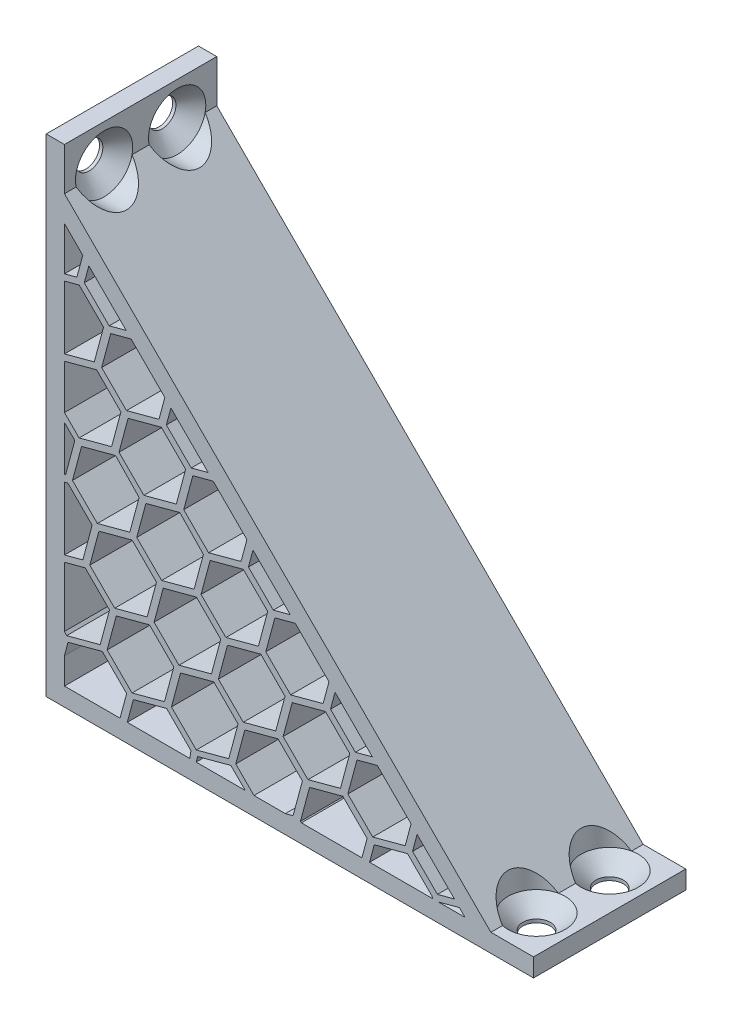
SolidWorks part; units mm, degrees
ref_plane "Front Plane" through (0, 0, 0) normal (0, 0, 1) x (1, 0, 0)
ref_plane "Top Plane" through (0, 0, 0) normal (0, 1, 0) x (1, 0, 0)
ref_plane "Right Plane" through (0, 0, 0) normal (1, 0, 0) x (0, 0, -1)
sketch "Sketch1" plane through (0, 0, 0) normal (0, 0, 1) x (1, 0, 0)
  line L0 (0, 0) -> (80, 0)
  line L1 (80, 0) -> (80, 3)
  line L2 (80, 3) -> (3, 3)
  line L3 (3, 3) -> (3, 80)
  line L4 (3, 80) -> (0, 80)
  line L5 (0, 80) -> (0, 0)
  line L6 (3, 73) -> (73, 3)
  line L25 (6.2553, 61.9666) -> (7.0024, 64.755)
  line L28 (3, 61.612) -> (5.0439, 62.1596)
  line L29 (5.0439, 62.1596) -> (6.0063, 65.7511)
  line L32 (7.0024, 64.755) -> (6.2553, 61.9666)
  line L33 (6.2553, 61.9666) -> (10.3377, 57.8841)
  line L34 (10.3377, 57.8841) -> (13.1261, 58.6312)
  line L40 (5.4254, 61.2266) -> (9.4181, 57.2339)
  line L41 (10.5966, 56.9182) -> (13.9426, 57.8147)
  line L55 (13.9426, 57.8147) -> (10.5966, 56.9182)
  line L56 (10.5966, 56.9182) -> (9.1023, 51.3414)
  line L57 (9.1023, 51.3414) -> (13.1848, 47.2589)
  line L58 (13.1848, 47.2589) -> (18.5161, 48.6874)
  line L59 (18.5161, 48.6874) -> (19.4784, 52.2789)
  line L62 (13.1261, 58.6312) -> (10.3377, 57.8841)
  line L63 (9.4181, 57.2339) -> (7.8909, 51.5344)
  line L64 (8.2725, 50.6014) -> (12.2651, 46.6087)
  line L65 (13.4436, 46.293) -> (18.8976, 47.7544)
  line L66 (19.7275, 48.4944) -> (20.4746, 51.2828)
  line L68 (20.4746, 51.2828) -> (19.7275, 48.4944)
  line L69 (19.7275, 48.4944) -> (23.8099, 44.4119)
  line L70 (23.8099, 44.4119) -> (26.5983, 45.159)
  line L75 (19.4784, 52.2789) -> (18.5161, 48.6874)
  line L76 (18.8976, 47.7544) -> (22.8903, 43.7617)
  line L77 (24.0688, 43.446) -> (27.4148, 44.3425)
  line L79 (18.8976, 47.7544) -> (13.4436, 46.293)
  line L80 (13.4436, 46.293) -> (11.9493, 40.7162)
  line L81 (11.9493, 40.7162) -> (16.0318, 36.6337)
  line L82 (16.0318, 36.6337) -> (21.3631, 38.0623)
  line L83 (21.3631, 38.0623) -> (22.8903, 43.7617)
  line L84 (22.8903, 43.7617) -> (18.8976, 47.7544)
  line L85 (23.8099, 44.4119) -> (19.7275, 48.4944)
  line L86 (18.5161, 48.6874) -> (13.1848, 47.2589)
  line L87 (12.2651, 46.6087) -> (10.7379, 40.9093)
  line L88 (11.3839, 39.9711) -> (15.2538, 35.9456)
  line L89 (16.3614, 35.6488) -> (21.9382, 37.1431)
  line L90 (22.5745, 37.8692) -> (24.0688, 43.446)
  line L91 (27.4148, 44.3425) -> (24.0688, 43.446)
  line L92 (24.0688, 43.446) -> (22.5745, 37.8692)
  line L93 (22.5745, 37.8692) -> (26.6569, 33.7867)
  line L94 (26.6569, 33.7867) -> (31.9883, 35.2152)
  line L95 (31.9883, 35.2152) -> (32.9506, 38.8067)
  line L98 (26.5983, 45.159) -> (23.8099, 44.4119)
  line L99 (22.8903, 43.7617) -> (21.3631, 38.0623)
  line L100 (21.9382, 37.1431) -> (25.8082, 33.1176)
  line L101 (26.9158, 32.8208) -> (32.3698, 34.2822)
  line L102 (33.1996, 35.0222) -> (33.9468, 37.8106)
  line L103 (5.4254, 61.2266) -> (3, 60.5767)
  line L106 (3, 50.2239) -> (7.8909, 51.5344)
  line L107 (7.8909, 51.5344) -> (9.4181, 57.2339)
  line L108 (9.4181, 57.2339) -> (5.4254, 61.2266)
  line L109 (10.3377, 57.8841) -> (6.2553, 61.9666)
  line L113 (3, 49.1886) -> (8.2725, 50.6014)
  line L114 (9.1023, 51.3414) -> (10.5966, 56.9182)
  line L115 (8.2725, 50.6014) -> (3, 49.1886)
  line L117 (3, 41.8873) -> (5.4066, 39.4807)
  line L118 (5.4066, 39.4807) -> (10.7379, 40.9093)
  line L119 (10.7379, 40.9093) -> (12.2651, 46.6087)
  line L120 (12.2651, 46.6087) -> (8.2725, 50.6014)
  line L121 (13.1848, 47.2589) -> (9.1023, 51.3414)
  line L122 (7.8909, 51.5344) -> (3, 50.2239)
  line L124 (3, 40.4731) -> (4.6995, 38.7736)
  line L125 (5.8071, 38.4768) -> (11.3839, 39.9711)
  line L126 (11.9493, 40.7162) -> (13.4436, 46.293)
  line L127 (30.3526, 45.6474) -> (31.9964, 51.7818) [skipped]
  line L128 (6.0063, 65.7511) -> (5.0439, 62.1596)
  line L129 (20.9629, 55.0371) -> (26.5397, 56.5314) [skipped]
  line L130 (6.0401, 61.1635) -> (7.9319, 68.2237) construction
  line L132 (9.2099, 11.0324) -> (3.5717, 9.5217)
  line L133 (26.2943, 56.4656) -> (27.8215, 62.1651) [skipped]
  line L134 (27.5056, 56.2725) -> (29.1493, 62.407) [skipped]
  line L135 (3.5717, 9.5217) -> (3, 7.317)
  line L140 (12.1201, 3) -> (13.2025, 7.0398)
  line L141 (13.2025, 7.0398) -> (9.2099, 11.0324)
  line L142 (19.7642, 8.2044) -> (14.3101, 6.743)
  line L143 (16.731, 58.5619) -> (16.8804, 59.1196) [skipped]
  line L144 (14.3101, 6.743) -> (13.3072, 3)
  line L146 (2.9431, 73.2125) -> (-3.8718, 71.3865) construction
  line L148 (-3.8718, 71.3865) -> (-5.6649, 64.6944) construction
  line L149 (33.9468, 37.8106) -> (33.1996, 35.0222)
  line L150 (-5.6649, 64.6944) -> (-0.4067, 59.4361) construction
  line L151 (2.5784, 71.8518) -> (-2.8756, 70.3904) construction
  line L152 (-4.3042, 65.059) -> (-0.042, 60.7969) construction
  line L153 (-2.8756, 70.3904) -> (-4.3042, 65.059) construction
  line L154 (-0.4067, 59.4361) -> (6.0401, 61.1635) construction
  line L155 (33.1996, 35.0222) -> (37.2821, 30.9397)
  line L156 (-0.042, 60.7969) -> (5.0439, 62.1596) construction
  line L157 (5.0439, 62.1596) -> (3, 61.612)
  line L158 (3, 60.5767) -> (5.4254, 61.2266)
  line L160 (37.2821, 30.9397) -> (40.0705, 31.6868)
  line L161 (7.9319, 68.2237) -> (2.9431, 73.2125) construction
  line L166 (43.8248, 32.1752) -> (47.9073, 28.0927)
  line L176 (40.887, 30.8703) -> (37.5409, 29.9738)
  line L177 (37.5409, 29.9738) -> (36.0467, 24.397)
  line L178 (36.0467, 24.397) -> (40.1291, 20.3145)
  line L179 (40.1291, 20.3145) -> (45.4605, 21.743)
  line L180 (45.4605, 21.743) -> (46.4228, 25.3345)
  line L183 (47.419, 24.3384) -> (46.6718, 21.55)
  line L184 (46.6718, 21.55) -> (50.7543, 17.4675)
  line L185 (50.7543, 17.4675) -> (53.5427, 18.2147)
  line L194 (45.842, 20.81) -> (40.388, 19.3486)
  line L195 (40.388, 19.3486) -> (38.8937, 13.7718)
  line L196 (38.8937, 13.7718) -> (42.9761, 9.6893)
  line L197 (42.9761, 9.6893) -> (48.3075, 11.1179)
  line L198 (48.3075, 11.1179) -> (49.8347, 16.8173)
  line L199 (49.8347, 16.8173) -> (45.842, 20.81)
  line L200 (54.3592, 17.3982) -> (51.0131, 16.5016)
  line L201 (51.0131, 16.5016) -> (49.5188, 10.9248)
  line L202 (49.5188, 10.9248) -> (53.6013, 6.8423)
  line L203 (53.6013, 6.8423) -> (58.9327, 8.2709)
  line L204 (58.9327, 8.2709) -> (59.895, 11.8623)
  line L207 (60.8912, 10.8662) -> (60.144, 8.0778)
  line L208 (60.144, 8.0778) -> (64.2265, 3.9953)
  line L209 (64.2265, 3.9953) -> (67.0149, 4.7425)
  line L212 (48.689, 10.1848) -> (43.235, 8.7234)
  line L213 (43.235, 8.7234) -> (41.7407, 3.1466)
  line L214 (41.7407, 3.1466) -> (41.8873, 3)
  line L216 (51.8264, 3) -> (52.6817, 6.1922)
  line L217 (52.6817, 6.1922) -> (48.689, 10.1848)
  line L218 (59.3142, 7.3378) -> (53.8601, 5.8764)
  line L219 (53.8601, 5.8764) -> (53.0894, 3)
  line L223 (63.3069, 3.3452) -> (59.3142, 7.3378)
  line L224 (67.8314, 3.926) -> (64.4853, 3.0294)
  line L225 (64.4853, 3.0294) -> (64.4775, 3)
  line L230 (32.3698, 34.2822) -> (26.9158, 32.8208)
  line L231 (26.9158, 32.8208) -> (25.4215, 27.244)
  line L232 (25.4215, 27.244) -> (29.504, 23.1615)
  line L233 (29.504, 23.1615) -> (34.8353, 24.5901)
  line L234 (34.8353, 24.5901) -> (36.3625, 30.2895)
  line L235 (36.3625, 30.2895) -> (32.3698, 34.2822)
  line L236 (35.2168, 23.657) -> (29.7628, 22.1956)
  line L237 (29.7628, 22.1956) -> (28.2685, 16.6188)
  line L238 (28.2685, 16.6188) -> (32.351, 12.5363)
  line L239 (32.351, 12.5363) -> (37.6823, 13.9649)
  line L240 (37.6823, 13.9649) -> (39.2095, 19.6644)
  line L241 (39.2095, 19.6644) -> (35.2168, 23.657)
  line L242 (38.0639, 13.0318) -> (32.6098, 11.5704)
  line L243 (32.6098, 11.5704) -> (31.1155, 5.9936)
  line L244 (31.1155, 5.9936) -> (34.1091, 3)
  line L245 (39.2616, 3) -> (40.5293, 3.3397)
  line L246 (40.5293, 3.3397) -> (42.0565, 9.0392)
  line L247 (42.0565, 9.0392) -> (38.0639, 13.0318)
  line L248 (21.8155, 37.1102) -> (16.3614, 35.6488)
  line L249 (16.3614, 35.6488) -> (14.8671, 30.072)
  line L250 (14.8671, 30.072) -> (18.9496, 25.9896)
  line L251 (18.9496, 25.9896) -> (24.281, 27.4181)
  line L252 (24.281, 27.4181) -> (25.8082, 33.1176)
  line L253 (25.8082, 33.1176) -> (21.8155, 37.1102)
  line L254 (24.6625, 26.485) -> (19.2084, 25.0236)
  line L255 (19.2084, 25.0236) -> (17.7141, 19.4468)
  line L256 (17.7141, 19.4468) -> (21.7966, 15.3644)
  line L257 (21.7966, 15.3644) -> (27.128, 16.7929)
  line L258 (27.128, 16.7929) -> (28.6552, 22.4924)
  line L259 (28.6552, 22.4924) -> (24.6625, 26.485)
  line L260 (27.5095, 15.8599) -> (22.0554, 14.3984)
  line L261 (22.0554, 14.3984) -> (20.5611, 8.8217)
  line L262 (20.5611, 8.8217) -> (24.6436, 4.7392)
  line L263 (24.6436, 4.7392) -> (29.975, 6.1677)
  line L264 (29.975, 6.1677) -> (31.5022, 11.8672)
  line L265 (31.5022, 11.8672) -> (27.5095, 15.8599)
  line L266 (11.2612, 39.9382) -> (5.8071, 38.4768)
  line L267 (5.8071, 38.4768) -> (4.3128, 32.9001)
  line L268 (4.3128, 32.9001) -> (8.3953, 28.8176)
  line L269 (8.3953, 28.8176) -> (13.7266, 30.2461)
  line L270 (13.7266, 30.2461) -> (15.2538, 35.9456)
  line L271 (15.2538, 35.9456) -> (11.2612, 39.9382)
  line L272 (14.1082, 29.3131) -> (8.6541, 27.8517)
  line L273 (8.6541, 27.8517) -> (7.1598, 22.2749)
  line L274 (7.1598, 22.2749) -> (11.2423, 18.1924)
  line L275 (11.2423, 18.1924) -> (16.5736, 19.6209)
  line L276 (16.5736, 19.6209) -> (18.1008, 25.3204)
  line L277 (18.1008, 25.3204) -> (14.1082, 29.3131)
  line L278 (16.9552, 18.6879) -> (11.5011, 17.2265)
  line L279 (11.5011, 17.2265) -> (10.0068, 11.6497)
  line L280 (10.0068, 11.6497) -> (14.0893, 7.5672)
  line L281 (14.0893, 7.5672) -> (19.4207, 8.9957)
  line L282 (19.4207, 8.9957) -> (20.9478, 14.6952)
  line L283 (20.9478, 14.6952) -> (16.9552, 18.6879)
  line L288 (3.1723, 33.0741) -> (4.6995, 38.7736)
  line L289 (4.6995, 38.7736) -> (3, 40.4731)
  line L290 (3.5538, 32.1411) -> (3, 31.9927)
  line L293 (3, 21.6399) -> (6.0193, 22.449)
  line L294 (6.0193, 22.449) -> (7.5465, 28.1484)
  line L295 (7.5465, 28.1484) -> (3.5538, 32.1411)
  line L296 (6.4008, 21.5159) -> (3, 20.6047)
  line L299 (3.3509, 10.3459) -> (8.8663, 11.8238)
  line L300 (8.8663, 11.8238) -> (10.3935, 17.5233)
  line L301 (10.3935, 17.5233) -> (6.4008, 21.5159)
  line L304 (23.7569, 4.2117) -> (19.7642, 8.2044)
  line L305 (30.3186, 5.3764) -> (24.8645, 3.9149)
  line L306 (24.8645, 3.9149) -> (24.6193, 3)
  line L310 (32.6949, 3) -> (30.3186, 5.3764)
  line L311 (23.5841, 3) -> (23.7569, 4.2117)
  line L312 (63.4422, 3) -> (63.3069, 3.3452)
  line L313 (5.0439, 62.1596) -> (6.5711, 67.8591) construction
  line L314 (3, 10.7746) -> (3.3509, 10.3459)
  line L315 (3, 33.1419) -> (3.1723, 33.0741)
  line L316 (6.5711, 67.8591) -> (2.5784, 71.8518) construction
  line L317 (0.7068, 42.7663) -> (-4.7473, 41.3049) [skipped]
  line L318 (-4.7473, 41.3049) -> (-6.2416, 35.7281) [skipped]
  line L319 (-6.2416, 35.7281) -> (-2.1591, 31.6456) [skipped]
  line L320 (-1.9003, 30.6797) -> (-3.3945, 25.1029) [skipped]
  line L321 (-3.3945, 25.1029) -> (0.6879, 21.0204) [skipped]
  line L322 (-2.3431, 31.5963) -> (0.0285, 32.2318) [skipped]
  line L323 (0.9468, 20.0545) -> (-0.5475, 14.4777) [skipped]
  line L324 (-0.6823, 14.6125) -> (0.0778, 13.8524) [skipped]
  line L325 (12.8159, 1.1662) -> (16.8983, -2.9163) [skipped]
  line L326 (16.8983, -2.9163) -> (22.2297, -1.4878) [skipped]
  line L327 (23.3702, -1.6618) -> (27.4527, -5.7443) [skipped]
  line L328 (27.4527, -5.7443) -> (32.784, -4.3158) [skipped]
  line L329 (32.784, -4.3158) -> (34.3112, 1.3837) [skipped]
  line L330 (22.2297, -1.4878) -> (22.6385, 0.038) [skipped]
  line L331 (6.1599, -0.1376) -> (11.6754, 1.3403) [skipped]
  line L332 (45.8232, -0.9359) -> (51.1545, 0.4927) [skipped]
  line L333 (52.3659, 0.2996) -> (56.4483, -3.7829) [skipped]
  line L334 (56.4483, -3.7829) -> (61.7797, -2.3543) [skipped]
  line L335 (61.8126, -2.2316) -> (62.4258, 0.0569) [skipped]
  line L336 (62.991, -2.5474) -> (67.0735, -6.6299) [skipped]
  line L337 (67.0735, -6.6299) -> (72.4049, -5.2013) [skipped]
  line L338 (72.4049, -5.2013) -> (73.9321, 0.4981) [skipped]
  line L339 (45.3191, 37.7519) -> (43.8248, 32.1752) [skipped]
  line L340 (47.9073, 28.0927) -> (53.2387, 29.5212) [skipped]
  line L341 (58.7913, 24.2798) -> (57.297, 18.703) [skipped]
  line L342 (61.3795, 14.6205) -> (66.7109, 16.049) [skipped]
  line L344 (66.7109, 16.049) -> (68.238, 21.7485) [skipped]
  line L346 (64.2454, 25.7412) -> (58.7913, 24.2798) [skipped]
  line L347 (58.5325, 25.2457) -> (63.8639, 26.6742) [skipped]
  line L348 (63.8639, 26.6742) -> (65.391, 32.3737) [skipped]
  line L350 (54.45, 29.3282) -> (58.5325, 25.2457) [skipped]
  line L352 (53.2387, 29.5212) -> (54.7658, 35.2207) [skipped]
  line L353 (55.9443, 34.9049) -> (54.45, 29.3282) [skipped]
  line L354 (61.3984, 36.3664) -> (55.9443, 34.9049) [skipped]
  line L356 (50.7732, 39.2134) -> (45.3191, 37.7519) [skipped]
  line L358 (3, 68.7574) -> (68.7574, 3)
  line L361 (69.5908, 5.5466) -> (69.7534, 6.1537) [skipped]
  line L362 (56.1186, 19.0187) -> (56.3398, 19.8444) [skipped]
  line L364 (62.3692, 13.8504) -> (61.6383, 13.6546) [skipped]
  line L365 (57.297, 18.703) -> (61.3795, 14.6205) [skipped]
  line L367 (48.7238, 27.2762) -> (48.1661, 27.1268) [skipped]
  line L368 (42.6135, 32.3682) -> (42.8287, 33.1713) [skipped]
  line L370 (35.2516, 40.7484) -> (34.6939, 40.599) [skipped]
  line L371 (29.1413, 45.8404) -> (29.3236, 46.5208) [skipped]
  line L373 (15.6691, 59.3126) -> (15.8514, 59.993) [skipped]
  dimension "D7" = 4
  dimension "D1" = 80
  dimension "D2" = 80
  dimension "D3" = 3
  dimension "D4" = 3
  dimension "D5" = 45
  dimension "D6" = 70
  dimension "D13" = 3
  dimension "D8" = 4
  dimension "D10" = 3
  dimension "D9" = 3
  dimension "D11" = 4
  dimension "D12" = 2
extrude "Boss-Extrude1" add sketch "Sketch1" along normal blind 25
sketch "Sketch2" plane through (3, 0, 0) normal (1, 0, 0) x (0, 0, -1)
  line L0 (-18.5, 74) -> (-6.5, 74) construction
  line L1 (-25, 80) -> (0, 80) construction
  circle A0 centre (-18.5, 74) radius 2
  circle A1 centre (-6.5, 74) radius 2
  point P4 (-12.5, 74)
  point P7 (-12.5, 80)
  dimension "D1" = 4
  dimension "D2" = 12
  dimension "D3" = 4
  dimension "D4" = 6
extrude "Cut-Extrude1" cut sketch "Sketch2" against normal through all
hole_wizard "CSK for M4 Countersunk Flat Head Screw1" positions "Sketch3" profile "Sketch4" countersink size "M4" standard "ISO" end condition through all
sketch "Sketch3" plane through (3, 0, 0) normal (1, 0, 0) x (0, 0, -1)
  point P0 (-18.5, 74)
  point P3 (-6.5, 74)
sketch "Sketch4" plane through (3, 74, 18.5) normal (0, 1, 0) x (0, 0, -1)
  line L0 (0, 0) -> (0, 3)
  line L1 (0, 3) -> (2.25, 3)
  line L2 (2.25, 3) -> (2.25, 2.45)
  line L3 (2.25, 2.45) -> (4.7, 0)
  line L5 (4.7, 0) -> (0, 0)
  line L6 (-2.25, 2.45) -> (-4.7, 0) construction
  line L11 (0, -6.35) -> (0, 107.95) construction
  dimension "Thru Hole Dia." = 4.5
  dimension "Thru Hole Depth" = 3
  dimension "Near C'Sink Dia." = 9.4
  dimension "Near C'Sink Angle" = 90
sketch "Sketch5" plane through (3, 0, 0) normal (1, 0, 0) x (0, 0, -1)
  circle A1 centre (-18.5, 74) radius 4.7
  circle A2 centre (-6.5, 74) radius 4.7
extrude "Cut-Extrude2" cut sketch "Sketch5" along normal through all
ref_plane "Plane1" through (0, 0, 0) normal (0.7071, -0.7071, 0) x (-0.7071, -0.7071, 0)
mirror "Mirror1" about plane through (0, 0, 0) normal (0.7071, -0.7071, 0) of "CSK for M4 Countersunk Flat Head Screw1", "Cut-Extrude1", "Cut-Extrude2"
